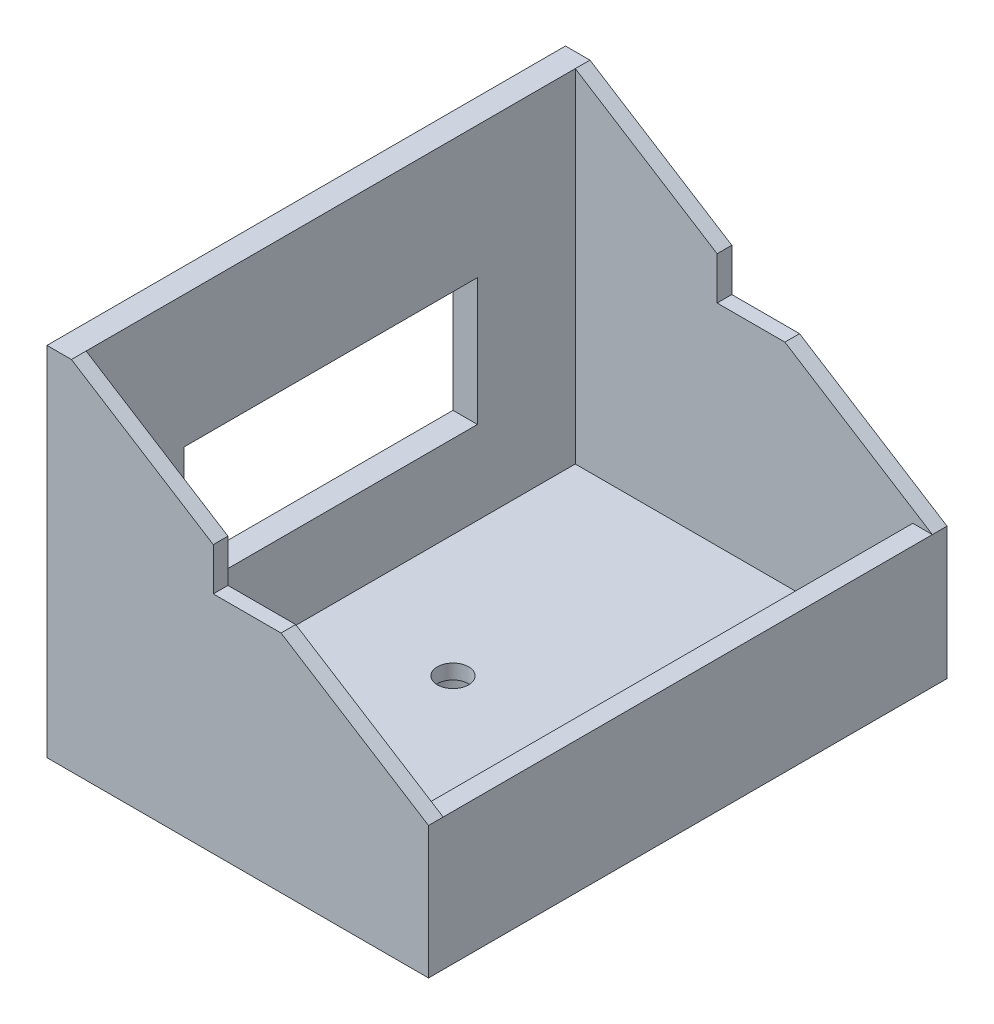
SolidWorks part; units mm, degrees
ref_plane "前视基准面" through (0, 0, 0) normal (0, 0, 1) x (1, 0, 0)
ref_plane "上视基准面" through (0, 0, 0) normal (0, 1, 0) x (1, 0, 0)
ref_plane "右视基准面" through (0, 0, 0) normal (1, 0, 0) x (0, 0, -1)
other "Configuration Table"
sketch "草图1" plane through (0, 0, 0) normal (0, 1, 0) x (1, 0, 0)
  line L0 (-38.4708, 0) -> (36.9052, 0) construction
  line L1 (0, 33.6043) -> (0, -32.9499) construction
  circle A0 centre (0, 0) radius 3.1
  circle A1 centre (0, 0) radius 4.5
  dimension "D1" = 6.2
  dimension "D2" = 9
extrude "凸台-拉伸1" add sketch "草图1" along normal blind 14.3
sketch "草图2" plane through (0, 14.3, 0) normal (0, 1, 0) x (1, 0, 0)
  line L1 (2.6, 1.6882) -> (2.6, -1.6882)
  circle A2 centre (0, 0) radius 3.1 construction
  arc A3 (2.6, -1.6882) -> (2.6, 1.6882) centre (0, 0) ccw
  dimension "D1" = 2.6
extrude "凸台-拉伸2" add sketch "草图2" against normal blind 11.25
sketch "草图4" plane through (0, 14.3, 0) normal (0, 1, 0) x (1, 0, 0)
  line L1 (-15, -25) -> (15, -25)
  line L2 (-15, -25) -> (-15, 25)
  line L3 (-15, 25) -> (15, 25)
  line L4 (15, -25) -> (15, 25)
  line L5 (-15, -25) -> (15, 25) construction
  line L6 (-15, 25) -> (15, -25) construction
  point P0 (0, 0)
  dimension "D1" = 50
  dimension "D2" = 30
extrude "凸台-拉伸3" add sketch "草图4" along normal blind 1.5
sketch "草图5" plane through (0, 15.8, 0) normal (0, 1, 0) x (1, 0, 0)
  circle A0 centre (0, 0) radius 1.6
  dimension "D1" = 3.2
extrude "切除-拉伸2" cut sketch "草图5" against normal through all
sketch "草图6" plane through (0, 15.8, 0) normal (0, 1, 0) x (1, 0, 0)
  line L0 (-15, 25) -> (-15, -25)
  line L1 (-15, -25) -> (-12.5, -25)
  line L2 (-15, -25) -> (15, -25) construction
  line L3 (-12.5, -25) -> (-12.5, 25)
  line L4 (15, 25) -> (-15, 25) construction
  line L5 (-12.5, 25) -> (-15, 25)
  dimension "D1" = 2.5
extrude "凸台-拉伸4" add sketch "草图6" along normal blind 35
sketch "草图7" plane through (-12.5, 0, 0) normal (1, 0, 0) x (0, 0, -1)
  line L0 (-37.1066, 30.8) -> (34.0914, 30.8) construction
  line L1 (0, 48.0932) -> (0, -10.4604) construction
  line L2 (-25, 15.8) -> (25, 15.8) construction
  line L4 (-15, 24.3) -> (15, 24.3)
  line L5 (-15, 24.3) -> (-15, 37.3)
  line L6 (-15, 37.3) -> (15, 37.3)
  line L7 (15, 24.3) -> (15, 37.3)
  line L8 (-15, 24.3) -> (15, 37.3) construction
  line L9 (-15, 37.3) -> (15, 24.3) construction
  point P7 (0, 30.8)
  dimension "D1" = 15
  dimension "D2" = 13
  dimension "D3" = 30
extrude "切除-拉伸3" cut sketch "草图7" against normal blind 10
sketch "草图9" plane through (0, 0, 0) normal (1, 0, 0) x (0, 0, -1)
  line L0 (0, 53.8351) -> (0, -14.9431) construction
  line L1 (-27, 14.3) -> (27, 14.3) construction
  circle A0 centre (0, 5.3) radius 1.55
  dimension "D2" = 3.1
  dimension "D1" = 9
extrude "切除-拉伸4" cut sketch "草图9" against normal through all and the other way through all
sketch "草图10" plane through (15, 0, 0) normal (1, 0, 0) x (0, 0, -1)
  line L4 (-25, 14.3) -> (25, 14.3)
  line L5 (25, 14.3) -> (25, 15.8)
  line L6 (25, 15.8) -> (-25, 15.8)
  line L7 (-25, 15.8) -> (-25, 14.3)
  line L8 (-25, 14.3) -> (25, 14.3)
  line L9 (25, 14.3) -> (25, 15.8)
  line L10 (25, 15.8) -> (-25, 15.8)
  line L11 (-25, 15.8) -> (-25, 14.3)
  dimension "D1" = 0
extrude "凸台-拉伸6" add sketch "草图10" along normal blind 9
sketch "草图12" plane through (0, 15.8, 0) normal (0, 1, 0) x (1, 0, 0)
  line L0 (24, 25) -> (24, -25) construction
  line L1 (24, 25) -> (24, -25)
  line L2 (24, 25) -> (22, 25)
  line L3 (24, 25) -> (-12.5, 25) construction
  line L4 (22, 25) -> (22, -25)
  line L5 (-12.5, -25) -> (24, -25) construction
  line L6 (22, -25) -> (24, -25)
  dimension "D1" = 2
extrude "凸台-拉伸7" add sketch "草图12" along normal blind 12
sketch "草图13" plane through (0, 0, 25) normal (0, 0, 1) x (1, 0, 0)
  line L1 (24, 27.8) -> (-12.5, 50.8)
  line L8 (-15, 14.3) -> (24, 14.3)
  line L9 (24, 14.3) -> (24, 27.8)
  line L10 (24, 27.8) -> (22, 27.8)
  line L11 (22, 27.8) -> (22, 15.8)
  line L12 (22, 15.8) -> (-12.5, 15.8)
  line L13 (-12.5, 15.8) -> (-12.5, 50.8)
  line L14 (-12.5, 50.8) -> (-15, 50.8)
  line L15 (-15, 50.8) -> (-15, 14.3)
  line L16 (-15, 14.3) -> (24, 14.3)
  line L17 (24, 14.3) -> (24, 27.8)
  line L22 (-12.5, 50.8) -> (-15, 50.8)
  line L23 (-15, 50.8) -> (-15, 14.3)
  dimension "D1" = 0
extrude "凸台-拉伸8" add sketch "草图13" along normal blind 1.5
mirror "镜向2" about plane through (0, 0, 0) normal (0, 0, 1) of "凸台-拉伸8"
sketch "草图14" plane through (0, 0, -26.5) normal (0, 0, -1) x (-1, 0, 0)
  line L0 (-24, 37.3) -> (-24, 50.8)
  line L1 (-2, 50.8) -> (-24, 50.8)
  line L2 (-24, 37.3) -> (-2, 37.3)
  line L3 (-2, 37.3) -> (-2, 50.8)
  line L4 (-24, 14.3) -> (-24, 27.8) construction
  line L7 (12.5, 50.8) -> (15, 50.8) construction
  dimension "D1" = 22
  dimension "D2" = 13.5
extrude "切除-拉伸5" cut sketch "草图14" against normal through all
